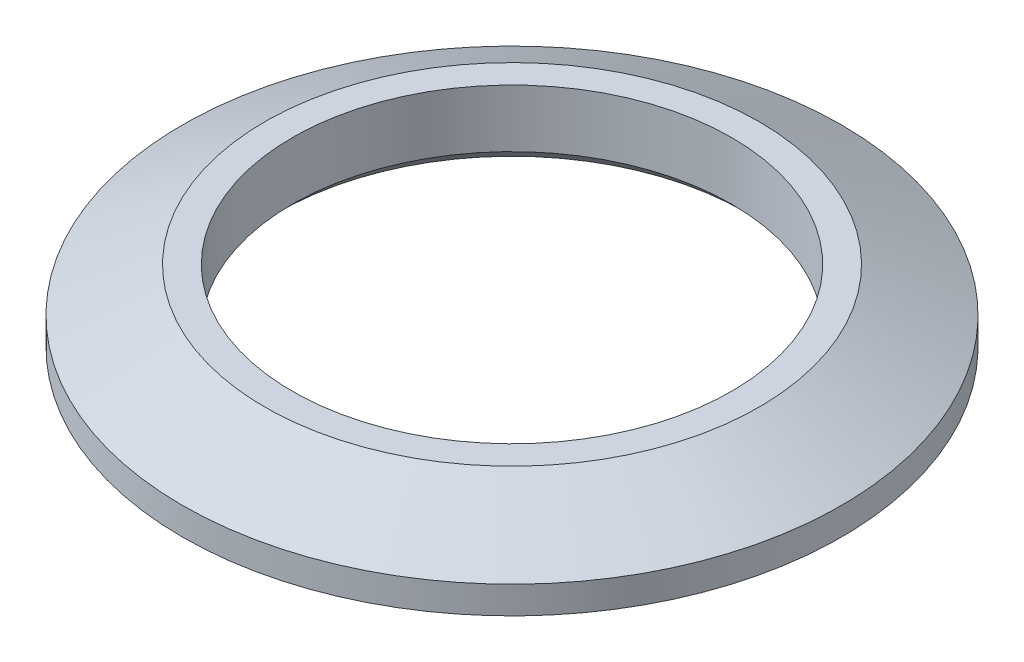
SolidWorks part; units mm, degrees
ref_plane "Front Plane" through (0, 0, 0) normal (0, 0, 1) x (1, 0, 0)
ref_plane "Top Plane" through (0, 0, 0) normal (0, 1, 0) x (1, 0, 0)
ref_plane "Right Plane" through (0, 0, 0) normal (1, 0, 0) x (0, 0, -1)
sketch "Sketch1" plane through (0, 0, 0) normal (0, 0, 1) x (1, 0, 0)
  line L0 (0, 0) -> (0, 2.5084) construction
  line L1 (-4, 0) -> (-4, 1.3)
  line L2 (-4, 1.3) -> (-4.5, 1.3)
  line L3 (-4.5, 1.3) -> (-6, 0.5)
  line L4 (-6, 0.5) -> (-6, 0)
  line L5 (-6, 0) -> (-4, 0)
  line L6 (-4.25, 0) -> (-4, 0.25)
  dimension "D1" = 1.3
  dimension "D2" = 4
  dimension "D3" = 0.5
  dimension "D4" = 2
  dimension "D5" = 0.25
  dimension "D6" = 0.25
  dimension "D7" = 0.5
revolve "Revolve1" add sketch "Sketch1" angle 360 about L0
